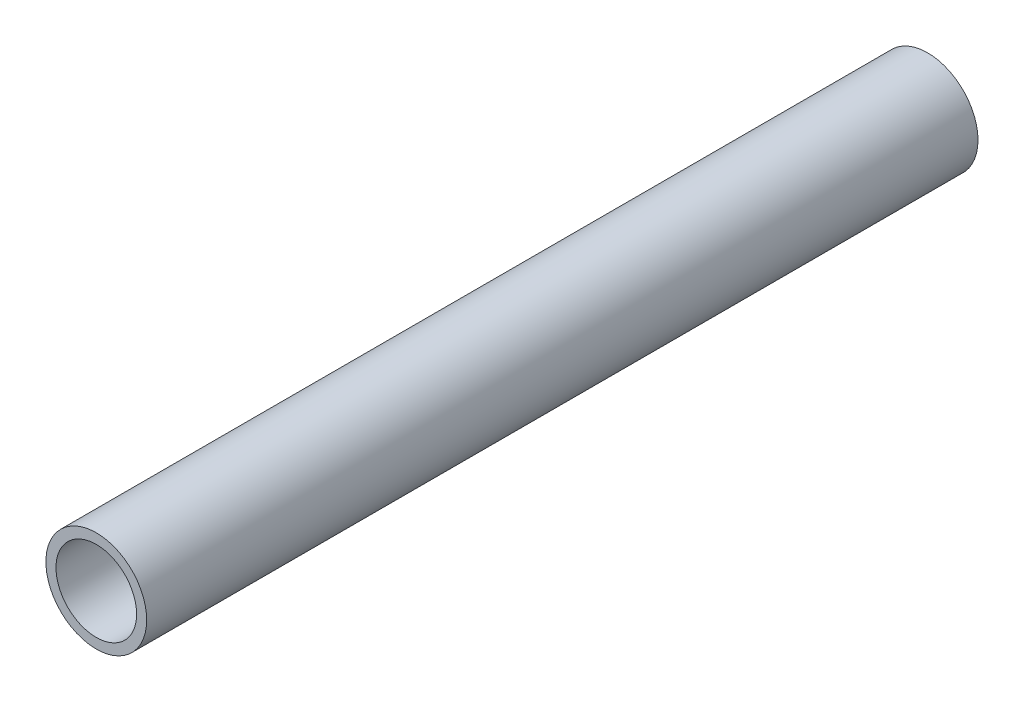
SolidWorks part; units mm, degrees
material "Thornel Mat VMA"
ref_plane "前视基准面" through (0, 0, 0) normal (0, 0, 1) x (1, 0, 0)
ref_plane "上视基准面" through (0, 0, 0) normal (0, 1, 0) x (1, 0, 0)
ref_plane "右视基准面" through (0, 0, 0) normal (1, 0, 0) x (0, 0, -1)
other "Configuration Table"
sketch "草图1" plane through (0, 0, 0) normal (0, 0, 1) x (1, 0, 0)
  circle A0 centre (0, 0) radius 10
  circle A1 centre (0, 0) radius 8
  dimension "D1" = 20
  dimension "D2" = 16
extrude "凸台-拉伸1" add sketch "草图1" along normal blind 165
